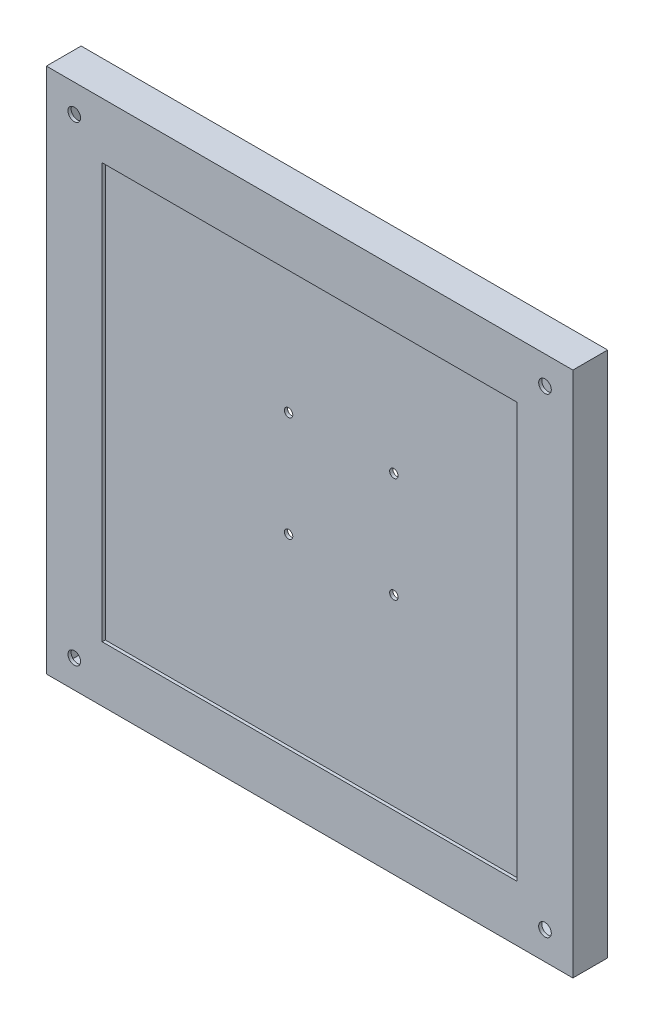
SolidWorks part; units mm, degrees
ref_plane "Front Plane" through (0, 0, 0) normal (0, 0, 1) x (1, 0, 0)
ref_plane "Top Plane" through (0, 0, 0) normal (0, 1, 0) x (1, 0, 0)
ref_plane "Right Plane" through (0, 0, 0) normal (1, 0, 0) x (0, 0, -1)
sketch "Sketch1" plane through (0, 0, 0) normal (0, 0, 1) x (1, 0, 0)
  line L1 (-250, -250) -> (250, -250)
  line L2 (-250, -250) -> (-250, 250)
  line L3 (-250, 250) -> (250, 250)
  line L4 (250, -250) -> (250, 250)
  line L5 (-250, -250) -> (250, 250) construction
  line L6 (-250, 250) -> (250, -250) construction
  point P0 (0, 0)
  dimension "D1" = 500
  dimension "D2" = 500
extrude "Boss-Extrude1" add sketch "Sketch1" along normal blind 3
sketch "Sketch3" plane through (0, 0, 0) normal (0, 0, -1) x (-1, 0, 0)
  line L0 (0, 250) -> (0, 0) construction
  line L1 (-250, 250) -> (250, 250) construction
  line L2 (0, 0) -> (250, 0) construction
  line L3 (250, 250) -> (250, -250) construction
  circle A0 centre (50, 50) radius 4
  circle A1 centre (-50, 50) radius 4
  circle A2 centre (50, -50) radius 4
  circle A3 centre (-50, -50) radius 4
  dimension "D3" = 8
  dimension "D1" = 100
  dimension "D2" = 100
extrude "Cut-Extrude1" cut sketch "Sketch3" against normal up to next
sketch "Sketch4" plane through (0, 0, 3) normal (0, 0, 1) x (1, 0, 0)
  line L4 (-247, 247) -> (-247, -247)
  line L9 (247, 247) -> (247, -247)
  line L12 (-247, 247) -> (247, 247)
  line L16 (-247, -247) -> (247, -247)
  line L18 (250, 250) -> (-250, 250)
  line L19 (250, 250) -> (250, -250)
  line L20 (250, -250) -> (-250, -250)
  line L21 (-250, 250) -> (-250, -250)
  line L22 (250, 250) -> (-250, -250) construction
  line L23 (250, -250) -> (-250, 250) construction
  point P0 (0, 0)
  dimension "D1" = 3
  dimension "D2" = 3
  dimension "D3" = 3
  dimension "D4" = 3
extrude "Boss-Extrude2" add sketch "Sketch4" along normal blind 30
sketch "Sketch5" plane through (0, 0, 33) normal (0, 0, 1) x (1, 0, 0)
  line L4 (-197, 197) -> (-197, -197)
  line L9 (197, 197) -> (197, -197)
  line L12 (-197, 197) -> (197, 197)
  line L16 (-197, -197) -> (197, -197)
  line L18 (-247, 247) -> (247, 247)
  line L19 (-247, 247) -> (-247, -247)
  line L20 (-247, -247) -> (247, -247)
  line L21 (247, 247) -> (247, -247)
  dimension "D1" = 50
  dimension "D2" = 50
  dimension "D3" = 50
  dimension "D4" = 50
extrude "Boss-Extrude3" add sketch "Sketch5" against normal blind 3
sketch "Sketch6" plane through (0, 0, 33) normal (0, 0, 1) x (1, 0, 0)
  line L0 (0, 250) -> (0, 0) construction
  line L1 (250, 250) -> (-250, 250) construction
  line L2 (0, 0) -> (250, 0) construction
  line L3 (250, -250) -> (250, 250) construction
  line L4 (-250, 250) -> (-197, 197) construction
  circle A0 centre (-223.5, 223.5) radius 6
  circle A1 centre (223.5, 223.5) radius 6
  circle A2 centre (223.5, -223.5) radius 6
  circle A3 centre (-223.5, -223.5) radius 6
  dimension "D1" = 12
extrude "Cut-Extrude2" cut sketch "Sketch6" against normal up to next
